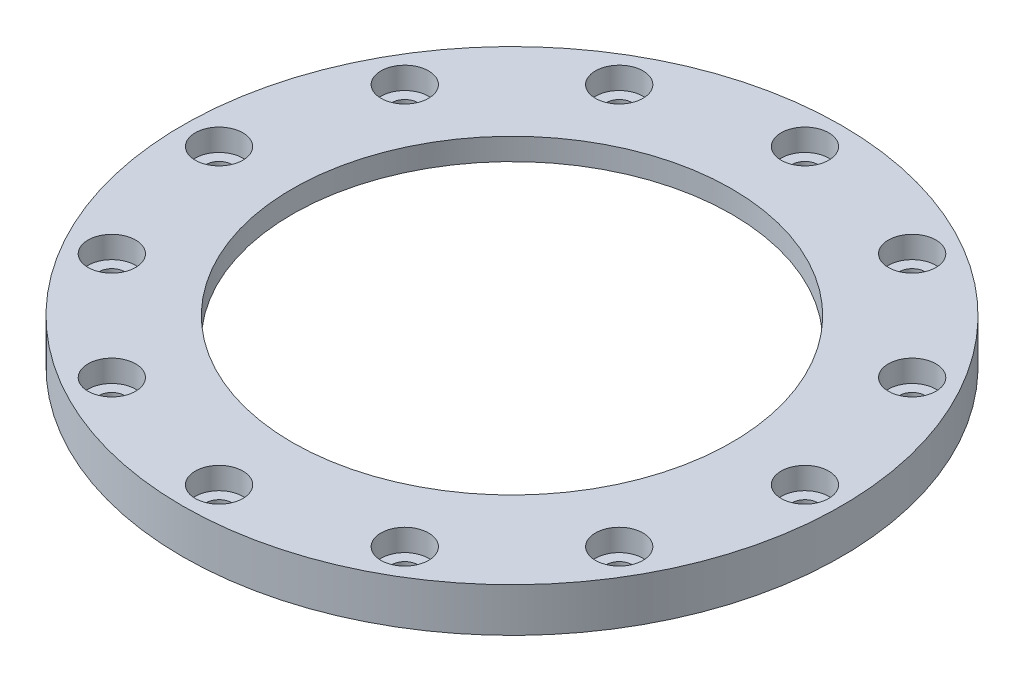
SolidWorks part; units mm, degrees
ref_plane "Front Plane" through (0, 0, 0) normal (0, 0, 1) x (1, 0, 0)
ref_plane "Top Plane" through (0, 0, 0) normal (0, 1, 0) x (1, 0, 0)
ref_plane "Right Plane" through (0, 0, 0) normal (1, 0, 0) x (0, 0, -1)
sketch "Sketch1" plane through (0, 0, 0) normal (0, 1, 0) x (1, 0, 0)
  line L0 (0, 0) -> (0, 52.0165) construction
  circle A0 centre (0, 0) radius 45
  circle A1 centre (0, 0) radius 30
  circle A2 centre (0, 0) radius 40 construction
  circle A3 centre (0, 40) radius 1.75
  circle A4 centre (0, 0) radius 36 construction
  circle A5 centre (20, 34.641) radius 1.75
  circle A6 centre (34.641, 20) radius 1.75
  circle A7 centre (40, 0) radius 1.75
  circle A8 centre (34.641, -20) radius 1.75
  circle A9 centre (20, -34.641) radius 1.75
  circle A10 centre (0, -40) radius 1.75
  circle A11 centre (-20, -34.641) radius 1.75
  circle A12 centre (-34.641, -20) radius 1.75
  circle A13 centre (-40, 0) radius 1.75
  circle A14 centre (-34.641, 20) radius 1.75
  circle A15 centre (-20, 34.641) radius 1.75
  point P21 (0, 0)
  point P34 (0, 0)
  point P48 (0, 0)
  point P72 (0, 0)
  dimension "D1" = 90
  dimension "D2" = 60
  dimension "D4" = 3.5
  dimension "D5" = 72
  dimension "D6" = 12
  dimension "D3" = 80
extrude "Boss-Extrude1" add sketch "Sketch1" along normal blind 6
sketch "Sketch2" plane through (0, 0, 0) normal (0, -1, 0) x (1, 0, 0)
  circle A0 centre (0, 0) radius 36
  dimension "D1" = 72
extrude "Cut-Extrude1" cut sketch "Sketch2" against normal blind 3
sketch "Sketch3" plane through (0, 6, 0) normal (0, 1, 0) x (1, 0, 0)
  line L0 (0, 0) -> (49.8808, 0) construction
  circle A0 centre (40, 0) radius 3.25
  circle A1 centre (34.641, -20) radius 3.25
  circle A2 centre (20, -34.641) radius 3.25
  circle A3 centre (0, -40) radius 3.25
  circle A4 centre (-20, -34.641) radius 3.25
  circle A5 centre (-34.641, -20) radius 3.25
  circle A6 centre (-40, 0) radius 3.25
  circle A7 centre (-34.641, 20) radius 3.25
  circle A8 centre (-20, 34.641) radius 3.25
  circle A9 centre (0, 40) radius 3.25
  circle A10 centre (20, 34.641) radius 3.25
  circle A11 centre (34.641, 20) radius 3.25
  point P30 (0, 0)
  dimension "D1" = 6.5
  dimension "D2" = 12
extrude "Cut-Extrude2" cut sketch "Sketch3" against normal blind 3
